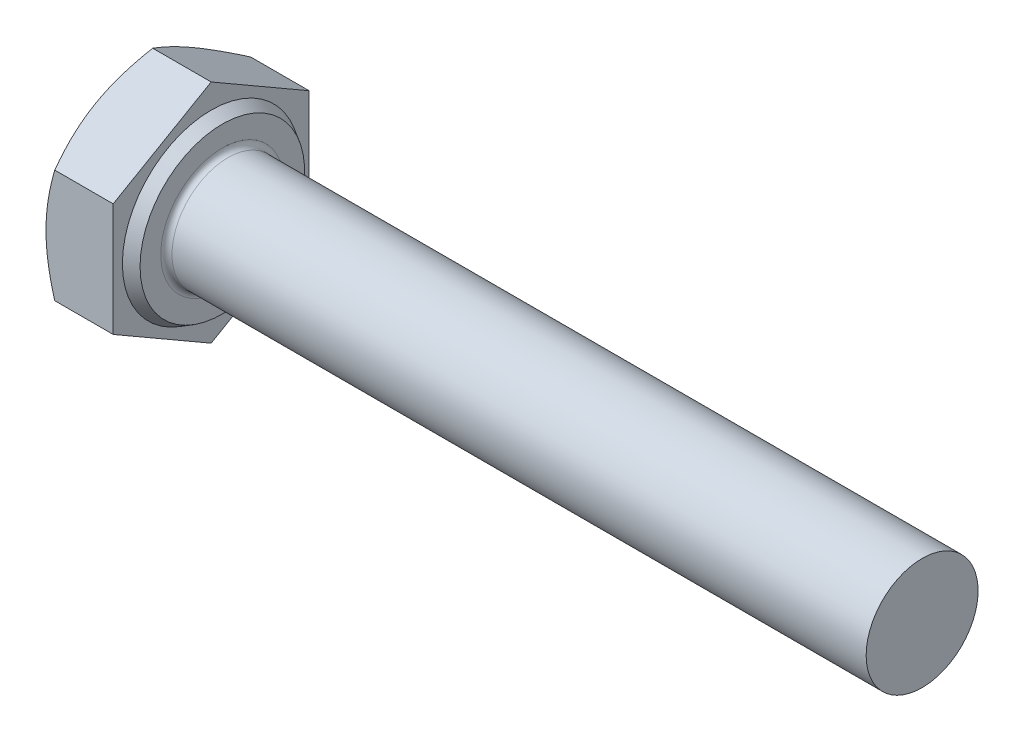
SolidWorks part; units mm, degrees
ref_plane "前视" through (0, 0, 0) normal (0, 0, 1) x (1, 0, 0)
ref_plane "上视" through (0, 0, 0) normal (0, 1, 0) x (1, 0, 0)
ref_plane "右视" through (0, 0, 0) normal (1, 0, 0) x (0, 0, -1)
sketch "草图1" plane through (0, 0, 0) normal (1, 0, 0) x (0, 0, -1)
  line L0 (3.5, 2.0207) -> (3.5, -2.0207)
  line L1 (-3.5, 2.0207) -> (-3.5, -2.0207)
  line L2 (3.5, -2.0207) -> (0, -4.0415)
  line L3 (0, -4.0415) -> (-3.5, -2.0207)
  line L4 (3.5, 2.0207) -> (0, 4.0415)
  line L5 (0, 4.0415) -> (-3.5, 2.0207)
  circle A0 centre (0, 0) radius 3.83 construction
  dimension "e" = 7.66
  dimension "s" = 7
  dimension "D2" = 120
  dimension "D3" = 3.5
  dimension "D4" = 3.5
  dimension "D5" = 3.5
extrude "基体-拉伸" add sketch "草图1" along normal blind 2.8
sketch "草图2" plane through (0, 0, 0) normal (0, 0, 1) x (1, 0, 0)
  line L0 (0, 2.0207) -> (0, -2.0207) construction
  line L1 (0, 0) -> (27.8, 0)
  line L2 (0, 0) -> (0, 2)
  line L3 (0, 2) -> (13.8, 2)
  line L4 (27.8, 0) -> (27.8, 1.3938)
  line L5 (2.8, 4.0415) -> (2.8, 2.0207) construction
  line L7 (0, 0) -> (31.8, 0) construction
  line L8 (27.8, -1.3938) -> (13.8, -2) construction
  line L9 (0, -2) -> (13.8, -2) construction
  line L10 (3.5, 2) -> (3.5, 0) construction
  line L11 (13.8, 15.24) -> (13.8, -1.27) construction
  line L12 (2.8, 2.0207) -> (2.8, -2.0207) construction
  line L13 (13.8, 2) -> (27.8, 2)
  line L14 (27.8, 2) -> (27.8, 1.3938)
  dimension "l" = 25
  dimension "d" = 4
  dimension "Minor_dia" = 2.7876
  dimension "p" = 0.7
  dimension "b" = 14
  dimension "ds" = 4
revolve "凸台-旋转1" add sketch "草图2" angle 360 about L7
cosmetic thread "螺旋线1" parameters "Thread_length"=14, "Thread_minor"=2.7876
sketch "草图3" plane through (0, 0, 0) normal (0, 0, 1) x (1, 0, 0)
  line L0 (0, 3.5) -> (3.1994, 9.0415)
  line L1 (0, 4.0415) -> (0, 2.0207) construction
  line L2 (3.1994, 9.0415) -> (3.1994, 14.0415)
  line L3 (3.1994, 14.0415) -> (-10, 14.0415)
  line L4 (-10, 14.0415) -> (-10, 3.5)
  line L5 (-10, 3.5) -> (0, 3.5)
  line L6 (0, 0) -> (99.06, 0) construction
  line L7 (2.8, 4.0415) -> (0, 4.0415) construction
  dimension "D1" = 3.5
  dimension "D2" = 5
  dimension "D3" = 10
  dimension "D4" = 5
  dimension "Head_ch_ang" = 30
revolve "切除-旋转1" cut sketch "草图3" angle 360 about L6
sketch "草图4" plane through (0, 0, 0) normal (0, 0, 1) x (1, 0, 0)
  line L0 (2.8, 0) -> (2.8, 2.94) construction
  line L2 (2.8, -2) -> (2.8, 2) construction
  line L3 (2.8, 4.0415) -> (2.8, 2.0207) construction
  line L4 (2.8, 2.94) -> (2.4, 3.1709)
  line L5 (0, 0) -> (95.25, 0) construction
  line L6 (0, 0) -> (31.8, 0) construction
  line L9 (2.4, 3.1709) -> (2.4, 4.0415)
  line L10 (2.8, 4.0415) -> (0.3126, 4.0415) construction
  line L11 (2.4, 4.0415) -> (2.8, 4.0415)
  line L12 (2.8, 4.0415) -> (2.8, 2.94)
  dimension "D1" = 120
  dimension "c" = 0.4
  dimension "dw" = 5.88
revolve "切除-旋转3" cut sketch "草图4" angle 360 about L5
fillet "圆角" radius 0.2 1 edges at (2.8, 0, -2)
sketch "草图6" plane through (0, 0, 0) normal (0, 0, 1) x (1, 0, 0)
  line L0 (0, 0) -> (27.8, 0) construction
  line L1 (27.8, -2) -> (27.8, 2) construction
  line L2 (27.8, 0) -> (27.8, 2) construction
  line L4 (27.45, 2) -> (28.15, 2)
  line L5 (27.45, 2) -> (27.8, 1.3938)
  line L6 (27.8, 1.3938) -> (28.15, 2)
  dimension "D1" = 0.7
revolve "切除-旋转4" [suppressed] cut sketch "草图6" angle 360 about L0
pattern_linear "阵列(线性)1" [suppressed]
